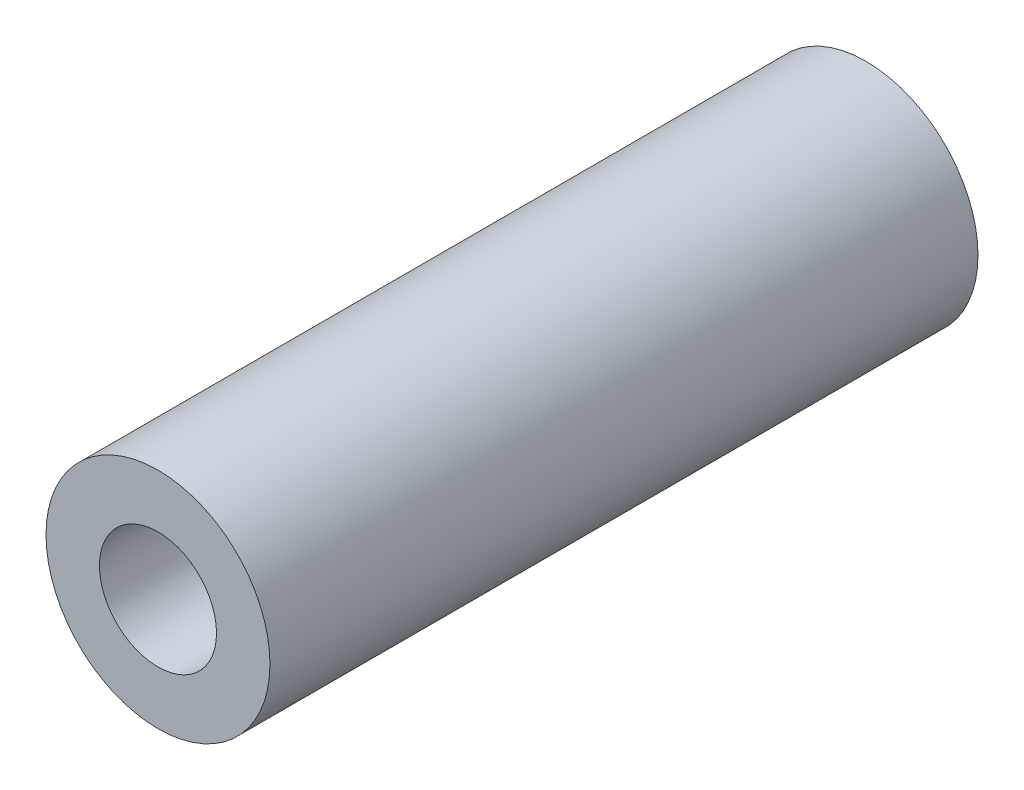
SolidWorks part; units mm, degrees
material "6061-T6 (SS)"
ref_plane "Front Plane" through (0, 0, 0) normal (0, 0, 1) x (1, 0, 0)
ref_plane "Top Plane" through (0, 0, 0) normal (0, 1, 0) x (1, 0, 0)
ref_plane "Right Plane" through (0, 0, 0) normal (1, 0, 0) x (0, 0, -1)
sketch "Sketch1" plane through (0, 0, 0) normal (0, 0, 1) x (1, 0, 0)
  circle A0 centre (0, 0) radius 4.7625
  circle A1 centre (0, 0) radius 2.4892
  dimension "D1" = 9.525
  dimension "D2" = 4.9784
extrude "Boss-Extrude1" add sketch "Sketch1" along normal mid plane 30.1117
